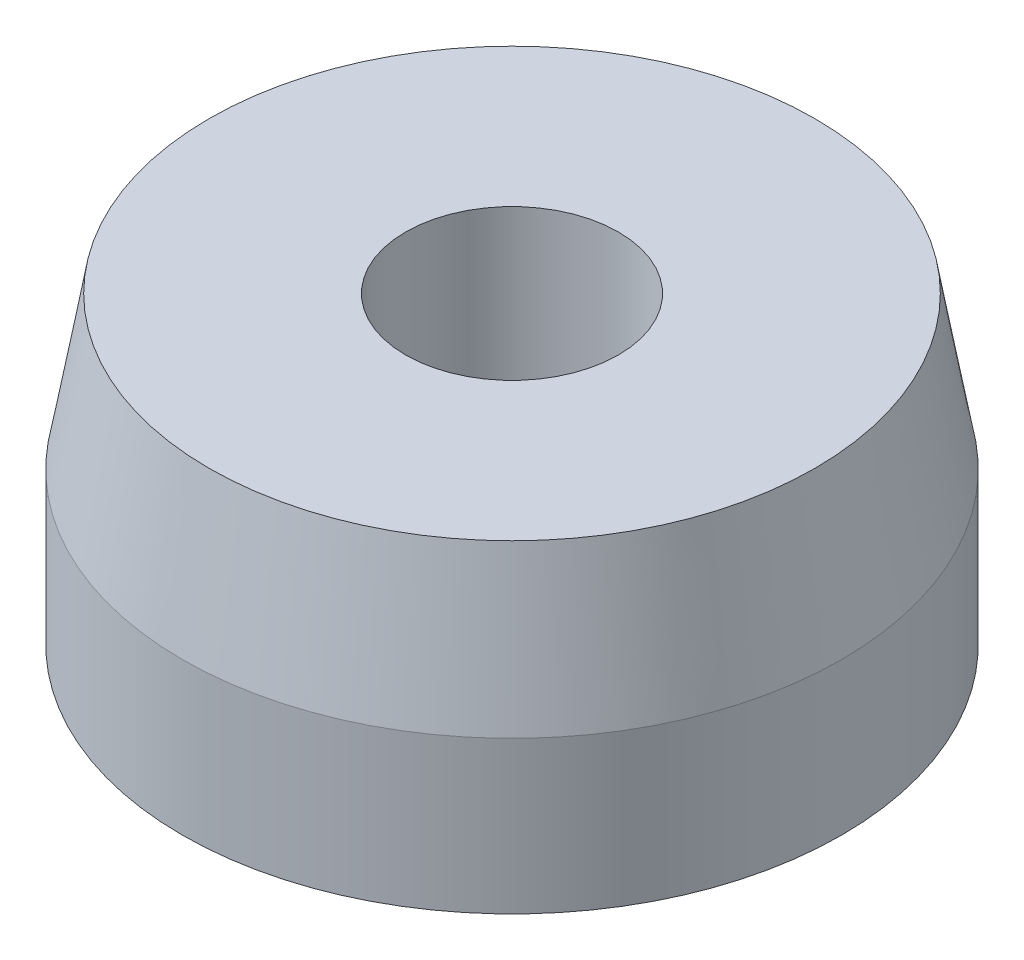
SolidWorks part; units mm, degrees
ref_plane "Front Plane" through (0, 0, 0) normal (0, 0, 1) x (1, 0, 0)
ref_plane "Top Plane" through (0, 0, 0) normal (0, 1, 0) x (1, 0, 0)
ref_plane "Right Plane" through (0, 0, 0) normal (1, 0, 0) x (0, 0, -1)
sketch "Sketch1" plane through (0, 0, 0) normal (0, 1, 0) x (1, 0, 0)
  circle A0 centre (0, 0) radius 13.25 construction
  circle A1 centre (0, 0) radius 3.5
  circle A2 centre (0, 0) radius 10.837
  dimension "D1" = 26.5
  dimension "D2" = 2.413
  dimension "D3" = 7
extrude "Boss-Extrude1" add sketch "Sketch1" along normal blind 10
chamfer "Chamfer1" distance 5 angle 10 1 edges at (0, 10, 10.837)
